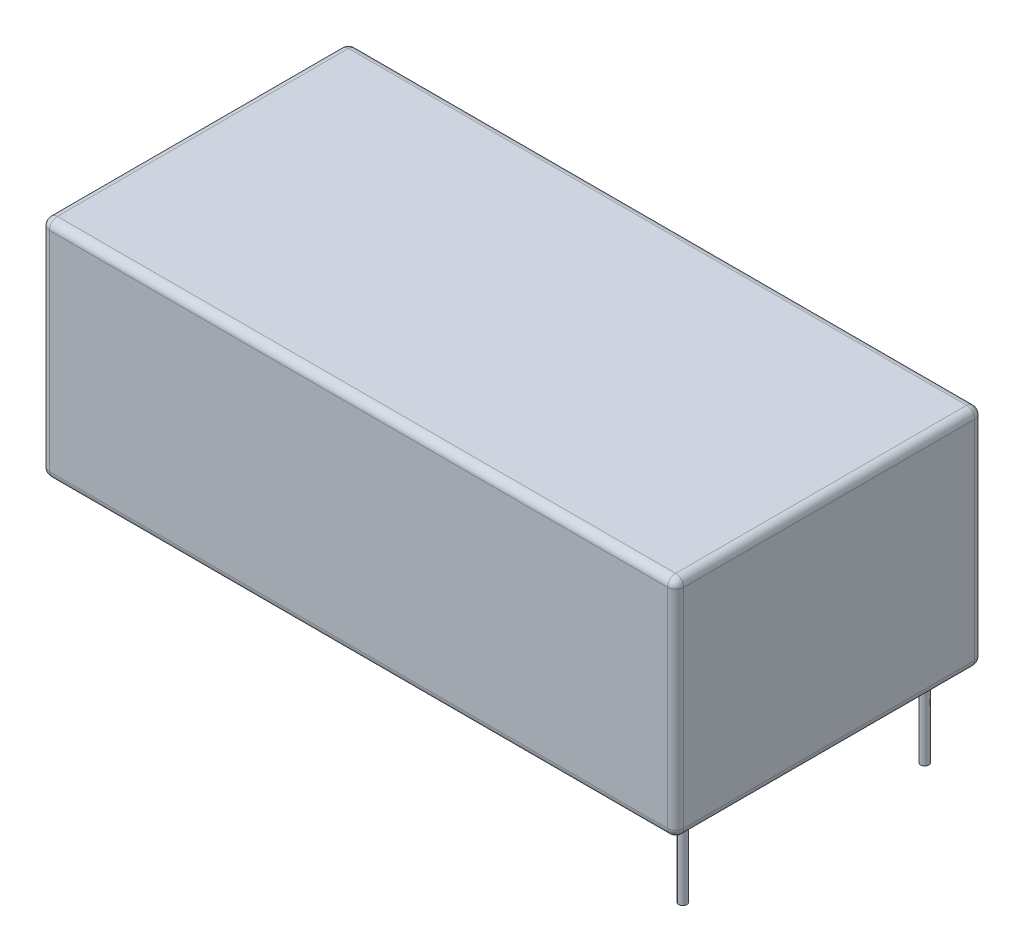
SolidWorks part; units mm, degrees
ref_plane "Front Plane" through (0, 0, 0) normal (0, 0, 1) x (1, 0, 0)
ref_plane "Top Plane" through (0, 0, 0) normal (0, 1, 0) x (1, 0, 0)
ref_plane "Right Plane" through (0, 0, 0) normal (1, 0, 0) x (0, 0, -1)
sketch "Sketch1" plane through (0, 0, 0) normal (0, 0, 1) x (1, 0, 0)
  line L1 (0, 0) -> (78.7, 0)
  line L2 (0, 0) -> (0, 27.9)
  line L3 (0, 27.9) -> (78.7, 27.9)
  line L4 (78.7, 0) -> (78.7, 27.9)
  dimension "D1" = 78.7
  dimension "D2" = 27.9
extrude "Boss-Extrude1" add sketch "Sketch1" along normal blind 38.1
sketch "Sketch2" plane through (0, 0, 0) normal (0, -1, 0) x (-1, 0, 0)
  line L0 (0, -4.1) -> (-78.7, -4.1) construction
  line L1 (0, -38.1) -> (0, 0) construction
  line L2 (-78.7, -38.1) -> (-78.7, 0) construction
  line L3 (0, 0) -> (-78.7, 0) construction
  line L4 (-3.2, -4.1) -> (-3.2, -38.1) construction
  line L5 (0, -38.1) -> (-78.7, -38.1) construction
  line L6 (-75.6, -4.1) -> (-75.6, -38.1) construction
  circle A0 centre (-3.2, -4.1) radius 0.5
  circle A1 centre (-75.6, -4.1) radius 0.5
  circle A2 centre (-75.6, -34.1) radius 0.5
  circle A3 centre (-3.2, -19.1) radius 0.5
  dimension "D2" = 1
  dimension "D4" = 1
  dimension "D6" = 1
  dimension "D8" = 1
  dimension "D1" = 4.1
  dimension "D3" = 72.4
  dimension "D5" = 3.2
  dimension "D7" = 30
  dimension "D9" = 15
extrude "Boss-Extrude2" add sketch "Sketch2" along normal blind 10
fillet "Fillet1" radius 1 12 edges at (39.35, 0, 0) (39.35, 27.9, 0) (78.7, 0, 19.05) (78.7, 27.9, 19.05) (78.7, 13.95, 0) (39.35, 27.9, 38.1) (78.7, 13.95, 38.1) (39.35, 0, 38.1) (0, 27.9, 19.05) (0, 13.95, 38.1) (0, 0, 19.05) (0, 13.95, 0)
